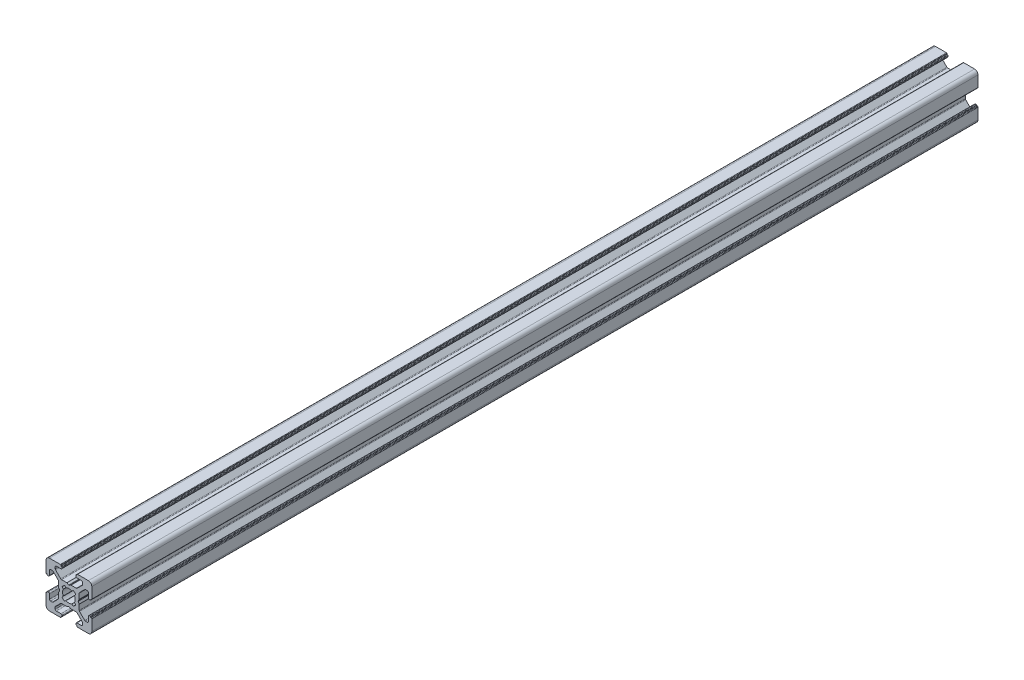
SolidWorks part; units mm, degrees
ref_plane "Front Plane" through (0, 0, 0) normal (0, 0, 1) x (1, 0, 0)
ref_plane "Top Plane" through (0, 0, 0) normal (0, 1, 0) x (1, 0, 0)
ref_plane "Right Plane" through (0, 0, 0) normal (1, 0, 0) x (0, 0, -1)
sketch "Sketch1" plane through (0, 0, 0) normal (0, 0, 1) x (1, 0, 0)
  line L0 (0, 13.3675) -> (0, -10.9159) construction
  line L1 (-12.9725, 0) -> (15.1887, 0) construction
  line L2 (-3.5, 8.5) -> (-5.5, 8.5)
  line L3 (-3.55, 9.7) -> (-3.55, 9.8)
  line L4 (-6, 7.2678) -> (-6, 8)
  line L5 (-7.2678, 6) -> (-8, 6)
  line L6 (-3.75, 10) -> (-8.5, 10)
  line L7 (-9.7, 3.55) -> (-9.8, 3.55)
  line L8 (-9.5, 3.2) -> (-9.5, 3.35)
  line L9 (-9, 3) -> (-9.3, 3)
  line L10 (-4.4732, 0.8536) -> (-4.0381, 0.1)
  line L11 (-4.5, 3.2322) -> (-4.5, 0.9536)
  line L12 (-8.5, 3.5) -> (-8.5, 5.5)
  line L13 (-10, 3.75) -> (-10, 8.5)
  line L14 (-3.5858, 4.6464) -> (-5.8536, 6.9142)
  line L15 (-4.6464, 3.5858) -> (-6.9142, 5.8536)
  line L16 (-3.2, 9.5) -> (-3.35, 9.5)
  line L17 (-3, 9) -> (-3, 9.3)
  line L18 (-0.8536, 4.4732) -> (-0.1, 4.0381)
  line L19 (-3.2322, 4.5) -> (-0.9536, 4.5)
  line L20 (-1.2582, 2.4453) -> (-1.9139, 2.9896)
  line L21 (-2.4453, 1.2582) -> (-2.9922, 1.9099)
  line L22 (3.5, -8.5) -> (5.5, -8.5)
  line L23 (3.55, -9.7) -> (3.55, -9.8)
  line L24 (6, -7.2678) -> (6, -8)
  line L25 (7.2678, -6) -> (8, -6)
  line L26 (3.75, -10) -> (8.5, -10)
  line L27 (9.7, -3.55) -> (9.8, -3.55)
  line L28 (9.5, -3.2) -> (9.5, -3.35)
  line L29 (9, -3) -> (9.3, -3)
  line L30 (4.4732, -0.8536) -> (4.0381, -0.1)
  line L31 (4.5, -3.2322) -> (4.5, -0.9536)
  line L32 (8.5, -3.5) -> (8.5, -5.5)
  line L33 (10, -3.75) -> (10, -8.5)
  line L34 (3.5858, -4.6464) -> (5.8536, -6.9142)
  line L35 (4.6464, -3.5858) -> (6.9142, -5.8536)
  line L36 (3.2, -9.5) -> (3.35, -9.5)
  line L37 (3, -9) -> (3, -9.3)
  line L38 (0.8536, -4.4732) -> (0.1, -4.0381)
  line L39 (3.2322, -4.5) -> (0.9536, -4.5)
  line L40 (1.2582, -2.4453) -> (1.9139, -2.9896)
  line L41 (2.4453, -1.2582) -> (2.9922, -1.9099)
  line L42 (-2.4453, -1.2582) -> (-2.9922, -1.9099)
  line L43 (-1.2582, -2.4453) -> (-1.9139, -2.9896)
  line L44 (-3.2322, -4.5) -> (-0.9536, -4.5)
  line L45 (-0.8536, -4.4732) -> (-0.1, -4.0381)
  line L46 (-3, -9) -> (-3, -9.3)
  line L47 (-3.2, -9.5) -> (-3.35, -9.5)
  line L48 (-4.6464, -3.5858) -> (-6.9142, -5.8536)
  line L49 (-3.5858, -4.6464) -> (-5.8536, -6.9142)
  line L50 (-10, -3.75) -> (-10, -8.5)
  line L51 (-8.5, -3.5) -> (-8.5, -5.5)
  line L52 (-4.5, -3.2322) -> (-4.5, -0.9536)
  line L53 (-4.4732, -0.8536) -> (-4.0381, -0.1)
  line L54 (-9, -3) -> (-9.3, -3)
  line L55 (-9.5, -3.2) -> (-9.5, -3.35)
  line L56 (-9.7, -3.55) -> (-9.8, -3.55)
  line L57 (2.4453, 1.2582) -> (2.9922, 1.9099)
  line L58 (1.2582, 2.4453) -> (1.9139, 2.9896)
  line L59 (3.2322, 4.5) -> (0.9536, 4.5)
  line L60 (0.8536, 4.4732) -> (0.1, 4.0381)
  line L61 (-3.75, -10) -> (-8.5, -10)
  line L62 (-7.2678, -6) -> (-8, -6)
  line L63 (-6, -7.2678) -> (-6, -8)
  line L64 (3, 9) -> (3, 9.3)
  line L65 (3.2, 9.5) -> (3.35, 9.5)
  line L66 (4.6464, 3.5858) -> (6.9142, 5.8536)
  line L67 (3.5858, 4.6464) -> (5.8536, 6.9142)
  line L68 (10, 3.75) -> (10, 8.5)
  line L69 (8.5, 3.5) -> (8.5, 5.5)
  line L70 (4.5, 3.2322) -> (4.5, 0.9536)
  line L71 (4.4732, 0.8536) -> (4.0381, 0.1)
  line L72 (9, 3) -> (9.3, 3)
  line L73 (9.5, 3.2) -> (9.5, 3.35)
  line L74 (9.7, 3.55) -> (9.8, 3.55)
  line L75 (3.75, 10) -> (8.5, 10)
  line L76 (7.2678, 6) -> (8, 6)
  line L77 (6, 7.2678) -> (6, 8)
  line L78 (3.55, 9.7) -> (3.55, 9.8)
  line L79 (3.5, 8.5) -> (5.5, 8.5)
  line L80 (-3.55, -9.7) -> (-3.55, -9.8)
  line L81 (-3.5, -8.5) -> (-5.5, -8.5)
  arc A0 (-10, 8.5) -> (-8.5, 10) centre (-8.5, 8.5) cw
  arc A1 (-8.5, 5.5) -> (-8, 6) centre (-8, 5.5) cw
  arc A2 (-7.2678, 6) -> (-6.9142, 5.8536) centre (-7.2678, 5.5) cw
  arc A3 (-5.8536, 6.9142) -> (-6, 7.2678) centre (-5.5, 7.2678) cw
  arc A4 (-6, 8) -> (-5.5, 8.5) centre (-5.5, 8) cw
  arc A5 (-9.7, 3.55) -> (-9.5, 3.35) centre (-9.7, 3.35) cw
  arc A6 (-9.8, 3.55) -> (-10, 3.75) centre (-9.8, 3.75) cw
  arc A7 (-9.3, 3) -> (-9.5, 3.2) centre (-9.3, 3.2) cw
  arc A8 (-8.5, 3.5) -> (-9, 3) centre (-9, 3.5) cw
  arc A9 (-4.6464, 3.5858) -> (-4.5, 3.2322) centre (-5, 3.2322) cw
  arc A10 (-4.4732, 0.8536) -> (-4.5, 0.9536) centre (-4.3, 0.9536) cw
  arc A11 (-4.0381, 0.1) -> (-4.0381, -0.1) centre (-4.2113, 0) cw
  arc A12 (-3.2, 9.5) -> (-3, 9.3) centre (-3.2, 9.3) cw
  arc A13 (-0.9536, 4.5) -> (-0.8536, 4.4732) centre (-0.9536, 4.3) cw
  arc A14 (-2.9922, 1.9099) -> (-1.9139, 2.9896) centre (0, 0) cw
  arc A15 (-3.2322, 4.5) -> (-3.5858, 4.6464) centre (-3.2322, 5) cw
  arc A16 (-3.75, 10) -> (-3.55, 9.8) centre (-3.75, 9.8) cw
  arc A17 (-3.35, 9.5) -> (-3.55, 9.7) centre (-3.35, 9.7) cw
  arc A18 (2.4453, -1.2582) -> (2.4453, 1.2582) centre (0, 0) ccw
  arc A19 (-3, 9) -> (-3.5, 8.5) centre (-3.5, 9) cw
  arc A20 (-2.4453, -1.2582) -> (-2.4453, 1.2582) centre (0, 0) cw
  arc A21 (10, -8.5) -> (8.5, -10) centre (8.5, -8.5) cw
  arc A22 (8.5, -5.5) -> (8, -6) centre (8, -5.5) cw
  arc A23 (7.2678, -6) -> (6.9142, -5.8536) centre (7.2678, -5.5) cw
  arc A24 (5.8536, -6.9142) -> (6, -7.2678) centre (5.5, -7.2678) cw
  arc A25 (6, -8) -> (5.5, -8.5) centre (5.5, -8) cw
  arc A26 (9.7, -3.55) -> (9.5, -3.35) centre (9.7, -3.35) cw
  arc A27 (9.8, -3.55) -> (10, -3.75) centre (9.8, -3.75) cw
  arc A28 (9.3, -3) -> (9.5, -3.2) centre (9.3, -3.2) cw
  arc A29 (8.5, -3.5) -> (9, -3) centre (9, -3.5) cw
  arc A30 (4.6464, -3.5858) -> (4.5, -3.2322) centre (5, -3.2322) cw
  arc A31 (4.4732, -0.8536) -> (4.5, -0.9536) centre (4.3, -0.9536) cw
  arc A32 (3.2, -9.5) -> (3, -9.3) centre (3.2, -9.3) cw
  arc A33 (-0.1, -4.0381) -> (0.1, -4.0381) centre (0, -4.2113) cw
  arc A34 (0.9536, -4.5) -> (0.8536, -4.4732) centre (0.9536, -4.3) cw
  arc A35 (2.9922, -1.9099) -> (1.9139, -2.9896) centre (0, 0) cw
  arc A36 (1.2582, -2.4453) -> (-1.2582, -2.4453) centre (0, 0) cw
  arc A37 (3.2322, -4.5) -> (3.5858, -4.6464) centre (3.2322, -5) cw
  arc A38 (3.75, -10) -> (3.55, -9.8) centre (3.75, -9.8) cw
  arc A39 (3.35, -9.5) -> (3.55, -9.7) centre (3.35, -9.7) cw
  arc A40 (3, -9) -> (3.5, -8.5) centre (3.5, -9) cw
  arc A41 (-3, -9) -> (-3.5, -8.5) centre (-3.5, -9) ccw
  arc A42 (-3.35, -9.5) -> (-3.55, -9.7) centre (-3.35, -9.7) ccw
  arc A43 (-3.75, -10) -> (-3.55, -9.8) centre (-3.75, -9.8) ccw
  arc A44 (-3.2322, -4.5) -> (-3.5858, -4.6464) centre (-3.2322, -5) ccw
  arc A45 (-2.9922, -1.9099) -> (-1.9139, -2.9896) centre (0, 0) ccw
  arc A46 (-0.9536, -4.5) -> (-0.8536, -4.4732) centre (-0.9536, -4.3) ccw
  arc A47 (-3.2, -9.5) -> (-3, -9.3) centre (-3.2, -9.3) ccw
  arc A48 (-4.4732, -0.8536) -> (-4.5, -0.9536) centre (-4.3, -0.9536) ccw
  arc A49 (3, 9) -> (3.5, 8.5) centre (3.5, 9) ccw
  arc A50 (3.35, 9.5) -> (3.55, 9.7) centre (3.35, 9.7) ccw
  arc A51 (3.75, 10) -> (3.55, 9.8) centre (3.75, 9.8) ccw
  arc A52 (3.2322, 4.5) -> (3.5858, 4.6464) centre (3.2322, 5) ccw
  arc A53 (1.2582, 2.4453) -> (-1.2582, 2.4453) centre (0, 0) ccw
  arc A54 (-4.6464, -3.5858) -> (-4.5, -3.2322) centre (-5, -3.2322) ccw
  arc A55 (-8.5, -3.5) -> (-9, -3) centre (-9, -3.5) ccw
  arc A56 (-9.3, -3) -> (-9.5, -3.2) centre (-9.3, -3.2) ccw
  arc A57 (-9.8, -3.55) -> (-10, -3.75) centre (-9.8, -3.75) ccw
  arc A58 (-9.7, -3.55) -> (-9.5, -3.35) centre (-9.7, -3.35) ccw
  arc A59 (-6, -8) -> (-5.5, -8.5) centre (-5.5, -8) ccw
  arc A60 (2.9922, 1.9099) -> (1.9139, 2.9896) centre (0, 0) ccw
  arc A61 (0.9536, 4.5) -> (0.8536, 4.4732) centre (0.9536, 4.3) ccw
  arc A62 (-0.1, 4.0381) -> (0.1, 4.0381) centre (0, 4.2113) ccw
  arc A63 (-5.8536, -6.9142) -> (-6, -7.2678) centre (-5.5, -7.2678) ccw
  arc A64 (-7.2678, -6) -> (-6.9142, -5.8536) centre (-7.2678, -5.5) ccw
  arc A65 (-8.5, -5.5) -> (-8, -6) centre (-8, -5.5) ccw
  arc A66 (-10, -8.5) -> (-8.5, -10) centre (-8.5, -8.5) ccw
  arc A67 (3.2, 9.5) -> (3, 9.3) centre (3.2, 9.3) ccw
  arc A68 (4.0381, 0.1) -> (4.0381, -0.1) centre (4.2113, 0) ccw
  arc A69 (4.4732, 0.8536) -> (4.5, 0.9536) centre (4.3, 0.9536) ccw
  arc A70 (4.6464, 3.5858) -> (4.5, 3.2322) centre (5, 3.2322) ccw
  arc A71 (8.5, 3.5) -> (9, 3) centre (9, 3.5) ccw
  arc A72 (9.3, 3) -> (9.5, 3.2) centre (9.3, 3.2) ccw
  arc A73 (9.8, 3.55) -> (10, 3.75) centre (9.8, 3.75) ccw
  arc A74 (9.7, 3.55) -> (9.5, 3.35) centre (9.7, 3.35) ccw
  arc A75 (6, 8) -> (5.5, 8.5) centre (5.5, 8) ccw
  arc A76 (5.8536, 6.9142) -> (6, 7.2678) centre (5.5, 7.2678) ccw
  arc A77 (7.2678, 6) -> (6.9142, 5.8536) centre (7.2678, 5.5) ccw
  arc A78 (8.5, 5.5) -> (8, 6) centre (8, 5.5) ccw
  arc A79 (10, 8.5) -> (8.5, 10) centre (8.5, 8.5) ccw
  dimension "D4" = 5.5
  dimension "D1" = 6
  dimension "D2" = 20
  dimension "D3" = 20
  dimension "D5" = 5.5
  dimension "D6" = 10
  dimension "D7" = 6
  dimension "D8" = 6
  dimension "D9" = 6
extrude "Extrude1" add sketch "Sketch1" along normal blind 387
